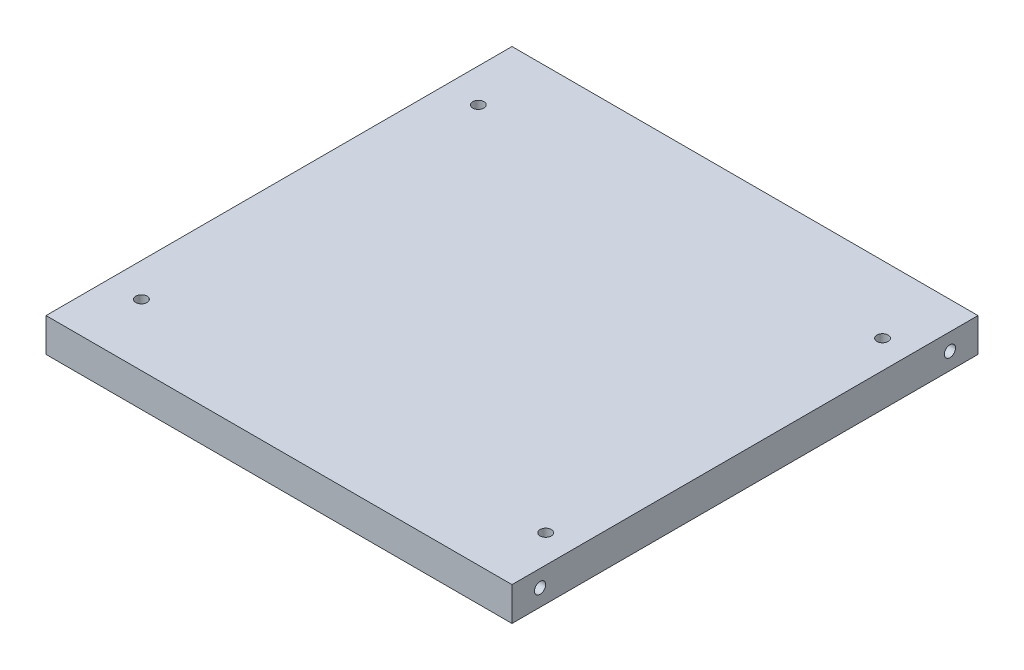
SolidWorks part; units mm, degrees
material "AISI 1020"
ref_plane "Front Plane" through (0, 0, 0) normal (0, 0, 1) x (1, 0, 0)
ref_plane "Top Plane" through (0, 0, 0) normal (0, 1, 0) x (1, 0, 0)
ref_plane "Right Plane" through (0, 0, 0) normal (1, 0, 0) x (0, 0, -1)
sketch "Sketch1" plane through (0, 0, 0) normal (0, 1, 0) x (1, 0, 0)
  line L1 (0, 0) -> (83, 0)
  line L2 (0, 0) -> (0, 83)
  line L3 (0, 83) -> (83, 83)
  line L4 (83, 0) -> (83, 83)
  dimension "D1" = 83
  dimension "D2" = 83
extrude "Boss-Extrude1" add sketch "Sketch1" along normal blind 6
sketch "Sketch2" plane through (0, 6, 0) normal (0, 1, 0) x (1, 0, 0)
  line L0 (83, 83) -> (0, 83) construction
  line L1 (0, 83) -> (0, 0) construction
  circle A0 centre (6, 71) radius 1
  dimension "D1" = 2
  dimension "D3" = 6
  dimension "D2" = 12
extrude "Cut-Extrude1" cut sketch "Sketch2" against normal blind 6
pattern_linear "LPattern1" count 2 spacing 72 along (1, 0, 0) count 2 spacing 60 along (0, 0, 1) of "Cut-Extrude1"
sketch "Sketch3" plane through (0, 0, 0) normal (-1, 0, 0) x (0, 0, 1)
  line L0 (-83, 3) -> (-5, 3) construction
  line L1 (-83, 6) -> (-83, 0) construction
  line L2 (0, 6) -> (0, 0) construction
  circle A0 centre (-78, 3) radius 1
  circle A1 centre (-5, 3) radius 1
  dimension "D1" = 5
  dimension "D3" = 2
  dimension "D4" = 2
  dimension "D2" = 5
extrude "Cut-Extrude2" cut sketch "Sketch3" against normal blind 10
ref_plane "Plane1" through (41.5, 0, 0) normal (-1, 0, 0) x (0, 0, 1)
mirror "Mirror1" about plane through (41.5, 0, 0) normal (-1, 0, 0) of "Cut-Extrude2"
